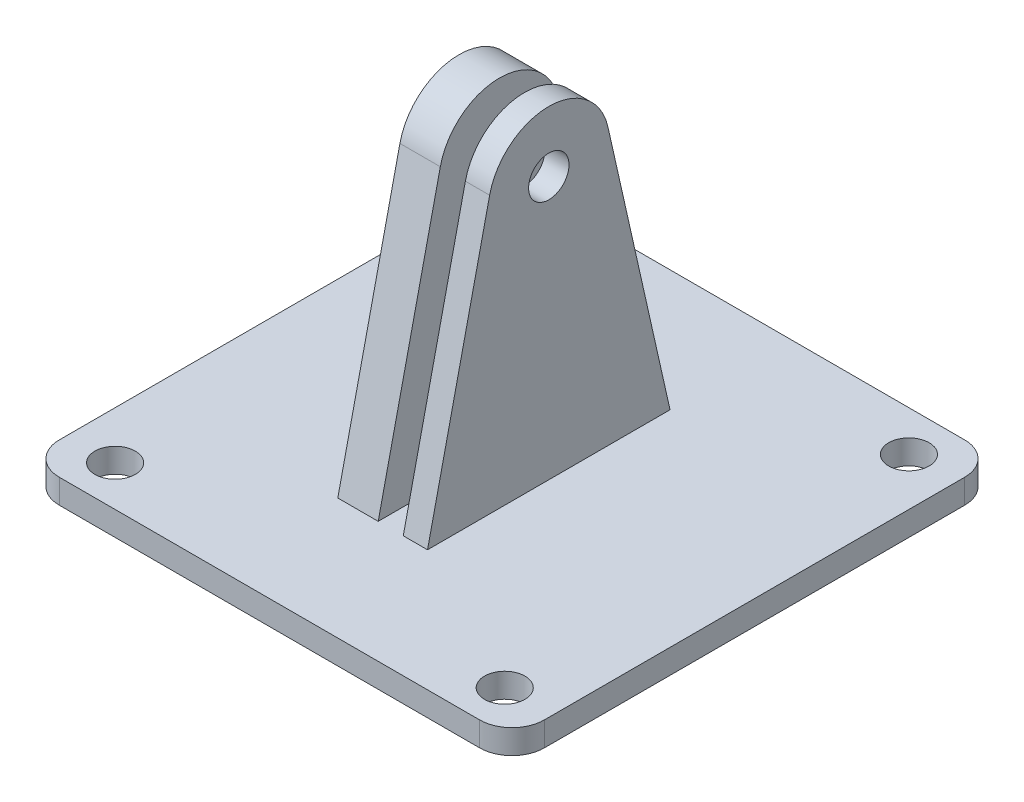
SolidWorks part; units mm, degrees
ref_plane "Front Plane" through (0, 0, 0) normal (0, 0, 1) x (1, 0, 0)
ref_plane "Top Plane" through (0, 0, 0) normal (0, 1, 0) x (1, 0, 0)
ref_plane "Right Plane" through (0, 0, 0) normal (1, 0, 0) x (0, 0, -1)
sketch "Sketch2" plane through (0, 0, 0) normal (0, 1, 0) x (1, 0, 0)
  line L1 (-26, -30) -> (26, -30)
  line L2 (-30, -26) -> (-30, 26)
  line L3 (-26, 30) -> (26, 30)
  line L4 (30, -26) -> (30, 26)
  line L5 (-30, -30) -> (30, 30) construction
  line L6 (-30, 30) -> (30, -30) construction
  circle A0 centre (-24.1, 25) radius 2.5
  circle A1 centre (24.1, 25) radius 2.5
  circle A2 centre (-24.1, -25) radius 2.5
  circle A3 centre (24.1, -25) radius 2.5
  arc A4 (26, 30) -> (30, 26) centre (26, 26) cw
  arc A5 (26, -30) -> (30, -26) centre (26, -26) ccw
  arc A6 (-26, -30) -> (-30, -26) centre (-26, -26) cw
  arc A7 (-30, 26) -> (-26, 30) centre (-26, 26) cw
  point P0 (0, 0)
  point P14 (0, 0)
  point P15 (0, 0)
  point P16 (0, 0)
  point P17 (0, 0)
  dimension "D4" = 5
  dimension "D5" = 5
  dimension "D6" = 5
  dimension "D7" = 5
  dimension "D11" = 4
  dimension "D1" = 60
  dimension "D2" = 60
  dimension "D3" = 24.1
  dimension "D8" = 24.1
  dimension "D9" = 5
  dimension "D10" = 5
extrude "Boss-Extrude1" add sketch "Sketch2" along normal blind 3
sketch "Sketch3" plane through (0, 3, 0) normal (0, 1, 0) x (1, 0, 0)
  line L1 (-15, -15) -> (15, -15)
  line L2 (-15, -15) -> (-15, 15)
  line L3 (-15, 15) -> (15, 15)
  line L4 (15, -15) -> (15, 15)
  line L5 (-15, -15) -> (15, 15) construction
  line L6 (-15, 15) -> (15, -15) construction
  point P0 (0, 0)
  dimension "D1" = 30
  dimension "D2" = 30
extrude "Boss-Extrude2" add sketch "Sketch3" along normal blind 40
sketch "Sketch6" plane through (0, 0, 0) normal (1, 0, 0) x (0, 0, -1)
  line L0 (-15, 43) -> (15, 43) construction
  line L1 (-7.3171, 37.1463) -> (-15, 3)
  line L2 (-15, 3) -> (15, 3) construction
  line L3 (7.3171, 37.1463) -> (15, 3)
  circle A0 centre (0, 35.5) radius 7.5
  point P11 (0, 0)
  point P13 (0, 0)
  dimension "D1" = 15
sketch "Sketch8" plane through (15, 0, 0) normal (1, 0, 0) x (0, 0, -1)
  line L0 (-7.3171, 37.1463) -> (-15, 3) construction
  line L1 (-7.3171, 37.1463) -> (-15, 3)
  line L2 (0, 43) -> (-15, 43)
  line L3 (-15, 43) -> (-15, 3)
  circle A0 centre (0, 35.5) radius 7.5 construction
  arc A1 (0, 43) -> (-7.3171, 37.1463) centre (0, 35.5) ccw
extrude "Cut-Extrude2" cut sketch "Sketch8" against normal blind 30
sketch "Sketch10" plane through (15, 0, 0) normal (1, 0, 0) x (0, 0, -1)
  line L0 (7.3171, 37.1463) -> (15, 3) construction
  line L1 (7.3171, 37.1463) -> (15, 3)
  line L2 (0, 43) -> (15, 43)
  line L3 (15, 43) -> (15, 3)
  circle A0 centre (0, 35.5) radius 7.5 construction
  arc A1 (7.3171, 37.1463) -> (0, 43) centre (0, 35.5) ccw
extrude "Cut-Extrude3" cut sketch "Sketch10" against normal blind 30
ref_plane "Plane1" through (0, 23, 0) normal (0, 1, 0) x (1, 0, 0)
sketch "Sketch12" plane through (0, 23, 0) normal (0, 1, 0) x (1, 0, 0)
  line L5 (0, -7.5) -> (0, 7.5) construction
  line L10 (1.55, -15) -> (-1.55, -15)
  line L11 (1.55, -15) -> (1.55, 15)
  line L12 (1.55, 15) -> (-1.55, 15)
  line L13 (-1.55, -15) -> (-1.55, 15)
  line L14 (1.55, -15) -> (-1.55, 15) construction
  line L15 (1.55, 15) -> (-1.55, -15) construction
  line L16 (15, 15) -> (-15, 15) construction
  line L17 (-15, -15) -> (15, -15) construction
  line L22 (-15, 15) -> (-6.55, 15)
  line L23 (-15, 15) -> (-15, -15)
  line L24 (-15, -15) -> (-6.55, -15)
  line L25 (-6.55, 15) -> (-6.55, -15)
  line L27 (15, 15) -> (4.55, 15)
  line L28 (15, 15) -> (15, -15)
  line L29 (15, -15) -> (4.55, -15)
  line L30 (4.55, 15) -> (4.55, -15)
  point P12 (0, 0)
  dimension "D1" = 5
  dimension "D2" = 3.1
  dimension "D3" = 3
extrude "Cut-Extrude4" cut sketch "Sketch12" along normal mid plane 40
sketch "Sketch13" plane through (0, 0, 0) normal (1, 0, 0) x (0, 0, -1)
  circle A1 centre (0, 35.5) radius 2.5
  dimension "D1" = 5
extrude "Cut-Extrude5" cut sketch "Sketch13" against normal mid plane 30
sketch "Sketch14" plane through (-6.55, 0, 0) normal (-1, 0, 0) x (0, 0, 1)
  line L1 (-3.5074, 37.525) -> (-3.5074, 33.475)
  line L2 (-3.5074, 33.475) -> (0, 31.45)
  line L3 (0, 31.45) -> (3.5074, 33.475)
  line L4 (3.5074, 33.475) -> (3.5074, 37.525)
  line L5 (3.5074, 37.525) -> (0, 39.55)
  line L6 (0, 39.55) -> (-3.5074, 37.525)
  circle A0 centre (0, 35.5) radius 3.5074 construction
  point P1 (-4.05, 35.5)
  point P10 (0, 31.45)
  point P11 (0, 0)
  point P12 (0, 0)
  dimension "D1" = 4.05
extrude "Cut-Extrude6" cut sketch "Sketch14" against normal blind 3
